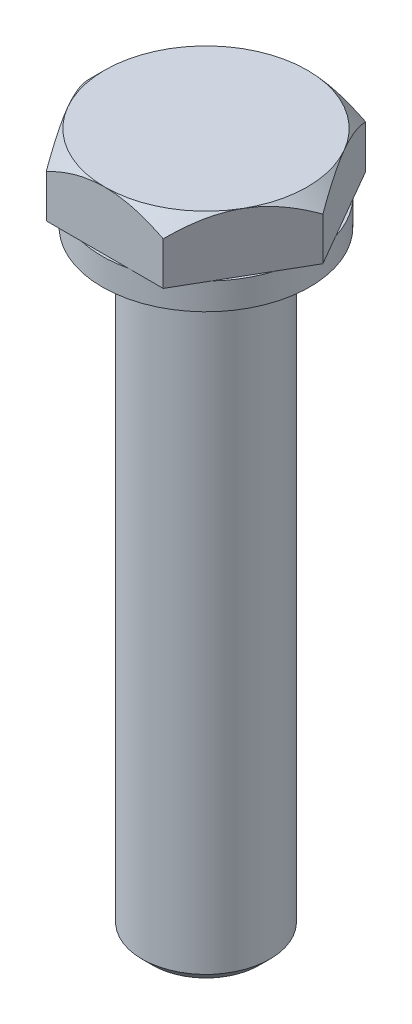
SolidWorks part; units mm, degrees
material "1.5714 (16NiCr4)"
ref_plane "Płaszczyzna przednia" through (0, 0, 0) normal (0, 0, 1) x (1, 0, 0)
ref_plane "Płaszczyzna górna" through (0, 0, 0) normal (0, 1, 0) x (1, 0, 0)
ref_plane "Płaszczyzna prawa" through (0, 0, 0) normal (1, 0, 0) x (0, 0, -1)
sketch "Szkic1" plane through (0, 0, 0) normal (0, 1, 0) x (1, 0, 0)
  circle A0 centre (0, 0) radius 6
  dimension "D1" = 12
extrude "Dodanie-wyciągnięcie1" add sketch "Szkic1" against normal blind 60
sketch "Szkic2" plane through (0, 0, 0) normal (0, 1, 0) x (1, 0, 0)
  line L1 (10.9697, 0) -> (5.4848, 9.5)
  line L2 (5.4848, 9.5) -> (-5.4848, 9.5)
  line L3 (-5.4848, 9.5) -> (-10.9697, 0)
  line L4 (-10.9697, 0) -> (-5.4848, -9.5)
  line L5 (-5.4848, -9.5) -> (5.4848, -9.5)
  line L6 (5.4848, -9.5) -> (10.9697, 0)
  circle A0 centre (0, 0) radius 9.5 construction
  dimension "D1" = 19
extrude "Dodanie-wyciągnięcie2" add sketch "Szkic2" along normal blind 5.5
sketch "Szkic3" plane through (0, 5.5, 0) normal (0, 1, 0) x (1, 0, 0)
  circle A0 centre (0, 0) radius 9.5
sketch "Szkic4" plane through (0, 0, 0) normal (0, 0, 1) x (1, 0, 0)
  line L0 (10.9697, 4.0303) -> (9.5, 5.5)
  line L2 (9.5, 5.5) -> (-9.5, 5.5) construction
  line L3 (9.5, 5.5) -> (10.9697, 5.5)
  line L4 (10.9697, 5.5) -> (10.9697, 4.0303)
sketch "Szkic5" plane through (0, 0, 0) normal (0, 0, 1) x (1, 0, 0)
  line L0 (0, 5.5) -> (0, -60) construction
  line L1 (9.5, 5.5) -> (-9.5, 5.5) construction
  line L2 (-6, -60) -> (6, -60) construction
revolve "Wycięcie-obrót1" cut sketch "Szkic4" angle 360 about L0
chamfer "Sfazowanie1" distance 1 angle 45 1 edges at (0, -60, 6)
sketch "Szkic6" plane through (0, 0, 0) normal (0, -1, 0) x (1, 0, 0)
  circle A0 centre (0, 0) radius 6.5
  circle A1 centre (0, 0) radius 9.75
  dimension "D1" = 13
  dimension "D2" = 19.5
extrude "Dodanie-wyciągnięcie3" add sketch "Szkic6" along normal blind 2.5
